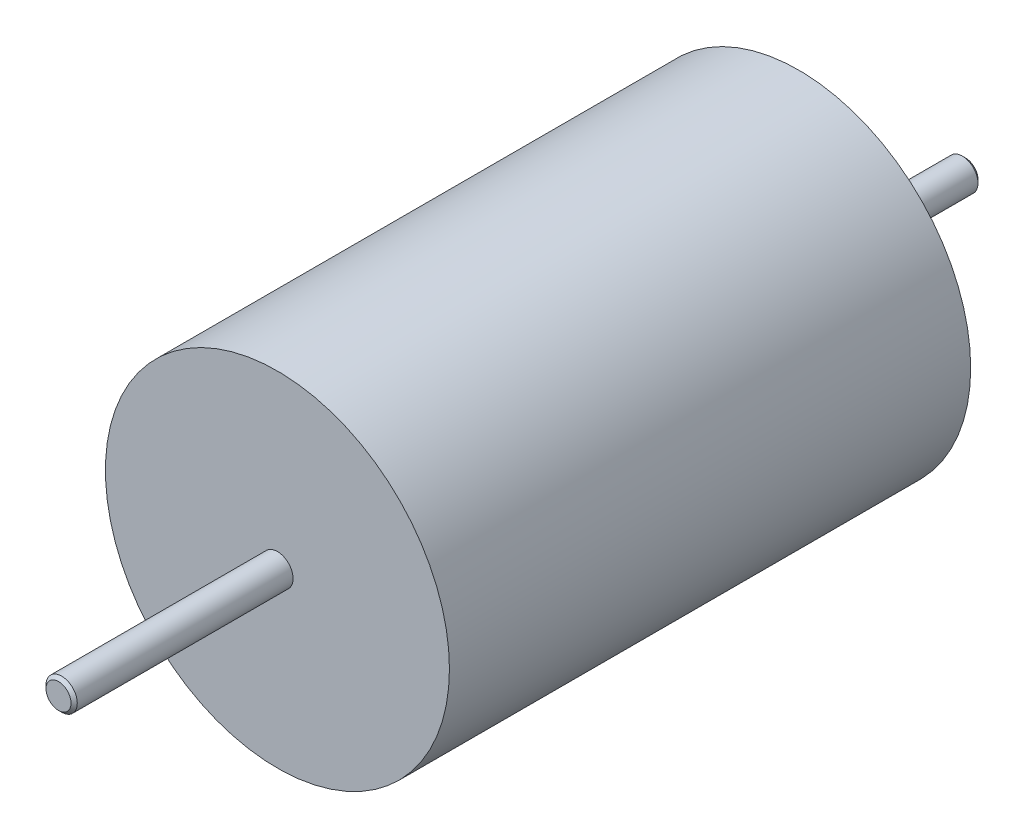
SolidWorks part; units mm, degrees
ref_plane "Front Plane" through (0, 0, 0) normal (0, 0, 1) x (1, 0, 0)
ref_plane "Top Plane" through (0, 0, 0) normal (0, 1, 0) x (1, 0, 0)
ref_plane "Right Plane" through (0, 0, 0) normal (1, 0, 0) x (0, 0, -1)
sketch "Sketch1" plane through (0, 0, 0) normal (0, 0, 1) x (1, 0, 0)
  circle A0 centre (0, 0) radius 1.5
  dimension "D1" = 3
extrude "Boss-Extrude1" add sketch "Sketch1" along normal mid plane 87
ref_plane "Plane1" through (0, 0, 22.5) normal (0, 0, 1) x (1, 0, 0)
sketch "Sketch4" plane through (0, 0, 22.5) normal (0, 0, 1) x (1, 0, 0)
  circle A0 centre (0, 0) radius 1.5 construction
  circle A1 centre (0, 0) radius 1.5
  circle A2 centre (0, 0) radius 16.5
  dimension "D1" = 33
extrude "Boss-Extrude2" add sketch "Sketch4" against normal blind 50
chamfer "Chamfer1" distance 0.3 angle 45 2 edges at (1.5, 0, -43.5) (1.5, 0, 43.5)
